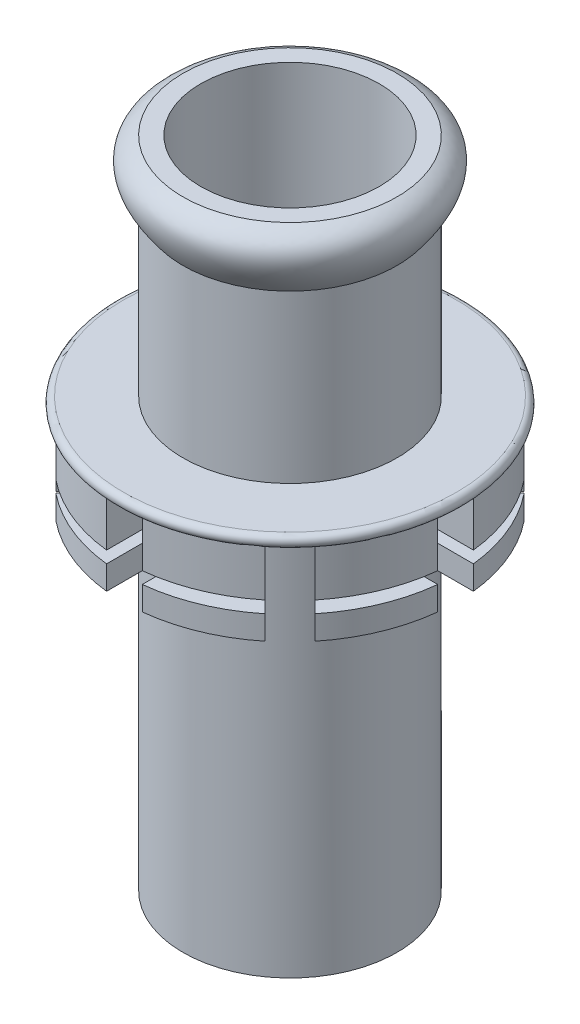
SolidWorks part; units mm, degrees
ref_plane "Piano frontale" through (0, 0, 0) normal (0, 0, 1) x (1, 0, 0)
ref_plane "Piano superiore" through (0, 0, 0) normal (0, 1, 0) x (1, 0, 0)
ref_plane "Piano destro" through (0, 0, 0) normal (1, 0, 0) x (0, 0, -1)
sketch "Schizzo2" plane through (0, 0, 0) normal (0, 0, 1) x (1, 0, 0)
  line L0 (0, 18.3588) -> (0, -150.8781) construction
  line L2 (-9, -21.1708) -> (-9, -7.1708)
  line L3 (-9, -21.1708) -> (-14, -21.1708)
  line L4 (-14, -26.1708) -> (-10, -26.1708)
  line L5 (-10, -26.1708) -> (-10, -27.1708)
  line L6 (-9, -29.1708) -> (-9, -57.1708)
  line L7 (-9, -57.1708) -> (-6, -57.1708)
  line L8 (-6, -57.1708) -> (-6, -29.6708)
  line L9 (-10, -27.1708) -> (-14, -27.1708)
  line L10 (-14, -27.1708) -> (-14, -29.1708)
  line L11 (-14, -22.1708) -> (-14, -26.1708)
  line L12 (-14, -29.1708) -> (-9, -29.1708)
  line L13 (0, -55) -> (0, 55) construction
  line L14 (16.5, 0) -> (-16.5, 0) construction
  line L15 (-6, -29.6708) -> (-7.5, -29.6708)
  line L16 (-7.5, -29.6708) -> (-7.5, -2.1708)
  line L17 (-7.5, -2.1708) -> (-9, -2.1708)
  arc A0 (-14, -21.1708) -> (-14, -22.1708) centre (-14, -21.6708) ccw
  spline S0 degree 2 poles (-9, -2.1708) (-11.9831, -3.357) (-9, -7.1708) knots 0 0 0 1 1 1
  dimension "D2" = 5
  dimension "D17" = 12
  dimension "D3" = 14
  dimension "D4" = 5
  dimension "D5" = 1
  dimension "D6" = 7
  dimension "D7" = 1
  dimension "D8" = 4
  dimension "D9" = 27.5
  dimension "D10" = 4
  dimension "D11" = 28
  dimension "D12" = 15
  dimension "D13" = 4.4515
  dimension "D14" = 4
  dimension "D15" = 57.1708
  dimension "D16" = 0.5
  dimension "D18" = 18
revolve "Rivoluzione1" add sketch "Schizzo2" angle 360 about L0
sketch "Schizzo5" plane through (0, -29.1708, 0) normal (0, -1, 0) x (1, 0, 0)
  line L0 (0, -55) -> (0, 55) construction
  line L1 (1.5, 15.0625) -> (-1.5, 15.0625)
  line L2 (1.5, 15.0625) -> (1.5, 8.8741)
  line L3 (0, 22.4763) -> (0, -19.319) construction
  line L4 (-1.5, 15.0625) -> (-1.5, 8.8741)
  line L5 (11.7114, 9.5901) -> (7.3356, 5.2143)
  line L6 (9.5901, 11.7114) -> (5.2143, 7.3356)
  line L7 (11.7114, 9.5901) -> (9.5901, 11.7114)
  line L8 (15.0625, -1.5) -> (8.8741, -1.5)
  line L9 (15.0625, 1.5) -> (8.8741, 1.5)
  line L10 (15.0625, -1.5) -> (15.0625, 1.5)
  line L11 (9.5901, -11.7114) -> (5.2143, -7.3356)
  line L12 (11.7114, -9.5901) -> (7.3356, -5.2143)
  line L13 (9.5901, -11.7114) -> (11.7114, -9.5901)
  line L14 (-1.5, -15.0625) -> (-1.5, -8.8741)
  line L15 (1.5, -15.0625) -> (1.5, -8.8741)
  line L16 (-1.5, -15.0625) -> (1.5, -15.0625)
  line L17 (-11.7114, -9.5901) -> (-7.3356, -5.2143)
  line L18 (-9.5901, -11.7114) -> (-5.2143, -7.3356)
  line L19 (-11.7114, -9.5901) -> (-9.5901, -11.7114)
  line L20 (-15.0625, 1.5) -> (-8.8741, 1.5)
  line L21 (-15.0625, -1.5) -> (-8.8741, -1.5)
  line L22 (-15.0625, 1.5) -> (-15.0625, -1.5)
  line L23 (-9.5901, 11.7114) -> (-5.2143, 7.3356)
  line L24 (-11.7114, 9.5901) -> (-7.3356, 5.2143)
  line L25 (-9.5901, 11.7114) -> (-11.7114, 9.5901)
  circle A2 centre (0, 0) radius 9 construction
  arc A3 (-1.5, 8.8741) -> (1.5, 8.8741) centre (0, 0) cw
  arc A4 (5.2143, 7.3356) -> (7.3356, 5.2143) centre (0, 0) cw
  arc A5 (8.8741, 1.5) -> (8.8741, -1.5) centre (0, 0) cw
  arc A6 (7.3356, -5.2143) -> (5.2143, -7.3356) centre (0, 0) cw
  arc A7 (1.5, -8.8741) -> (-1.5, -8.8741) centre (0, 0) cw
  arc A8 (-5.2143, -7.3356) -> (-7.3356, -5.2143) centre (0, 0) cw
  arc A9 (-8.8741, -1.5) -> (-8.8741, 1.5) centre (0, 0) cw
  arc A10 (-7.3356, 5.2143) -> (-5.2143, 7.3356) centre (0, 0) cw
  point P43 (0, 0)
  dimension "D1" = 1.5
  dimension "D2" = 1.5
  dimension "D4" = 6.1883
  dimension "D3" = 8
extrude "Taglio-Estrusione1" cut sketch "Schizzo5" against normal blind 7
